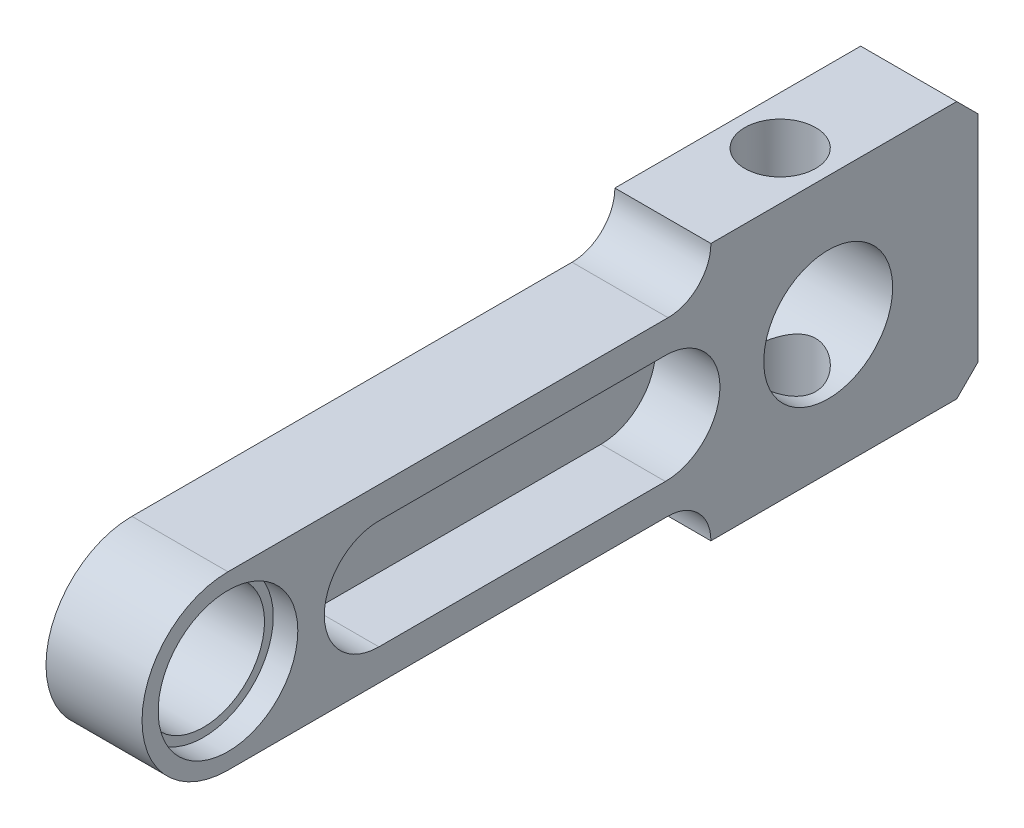
SolidWorks part; units mm, degrees
ref_plane "Front Plane" through (0, 0, 0) normal (0, 0, 1) x (1, 0, 0)
ref_plane "Top Plane" through (0, 0, 0) normal (0, 1, 0) x (1, 0, 0)
ref_plane "Right Plane" through (0, 0, 0) normal (1, 0, 0) x (0, 0, -1)
sketch "Sketch1" plane through (0, 0, 0) normal (1, 0, 0) x (0, 0, -1)
  line L0 (0, 0) -> (27.94, 0) construction
  line L1 (0, 4) -> (20.4856, 4)
  line L2 (0, -4) -> (20.4856, -4)
  line L4 (-4, 0) -> (-4, 8.8096) construction
  line L5 (34.9128, -5.0038) -> (34.9128, 5.0038)
  line L6 (22.48, -5.9944) -> (33.9222, -5.9944)
  line L7 (22.48, 5.9944) -> (33.9222, 5.9944)
  line L8 (0, 5.9944) -> (27.94, 5.9944) construction
  line L9 (34.9128, 0) -> (34.9128, 8.8096) construction
  line L10 (0, -5.9944) -> (27.94, -5.9944) construction
  line L14 (33.9222, 5.9944) -> (34.9128, 5.0038)
  line L16 (33.9222, -5.9944) -> (34.9128, -5.0038)
  arc A0 (0, 4) -> (0, -4) centre (0, 0) ccw
  arc A1 (20.4856, 4) -> (22.48, 5.9944) centre (20.4856, 5.9944) ccw
  circle A2 centre (0, 0) radius 2.8448
  circle A3 centre (27.94, 0) radius 3
  arc A4 (22.48, -5.9944) -> (20.4856, -4) centre (20.4856, -5.9944) ccw
  point P3 (13.97, 0)
  dimension "D1" = 27.94
  dimension "D2" = 4
  dimension "D3" = 5.6896
  dimension "D4" = 6
  dimension "D5" = 38.9128
  dimension "D6" = 5.9944
  dimension "D7" = 5.9944
extrude "Boss-Extrude1" add sketch "Sketch1" along normal blind 4.4704
sketch "Sketch2" plane through (4.4704, 0, 0) normal (1, 0, 0) x (0, 0, -1)
  circle A0 centre (0, 0) radius 3.2512
  dimension "D1" = 6.5024
sketch "Sketch4" plane through (4.4704, 0, 0) normal (1, 0, 0) x (0, 0, -1)
  line L1 (7.026, 0) -> (20.361, 0) construction
  line L2 (7.026, 2.54) -> (20.361, 2.54)
  line L3 (7.026, -2.54) -> (20.361, -2.54)
  arc A1 (7.026, 2.54) -> (7.026, -2.54) centre (7.026, 0) ccw
  arc A3 (20.361, -2.54) -> (20.361, 2.54) centre (20.361, 0) ccw
  point P8 (13.6935, 0)
  dimension "D1" = 2.54
  dimension "D2" = 13.335
extrude "Cut-Extrude1" cut sketch "Sketch2" against normal blind 1.143
extrude "Cut-Extrude2" cut sketch "Sketch4" against normal blind 2.9972
sketch "Sketch5" plane through (0, -5.9944, 0) normal (0, -1, 0) x (1, 0, 0)
  line L0 (2.2352, -24.94) -> (2.2352, -30.94) construction
  line L1 (4.4704, -24.94) -> (0, -24.94) construction
  line L2 (0, -30.94) -> (4.4704, -30.94) construction
  circle A0 centre (2.2352, -27.94) radius 1.651
  dimension "D1" = 3.302
extrude "Cut-Extrude3" cut sketch "Sketch5" against normal through all
sketch "Sketch6" plane through (4.4704, 0, 0) normal (1, 0, 0) x (0, 0, -1)
  line L0 (27.94, 0) -> (0, 0) construction
scale "Scale1" scale about centroid uniform scaling yes scale factor 0.6
